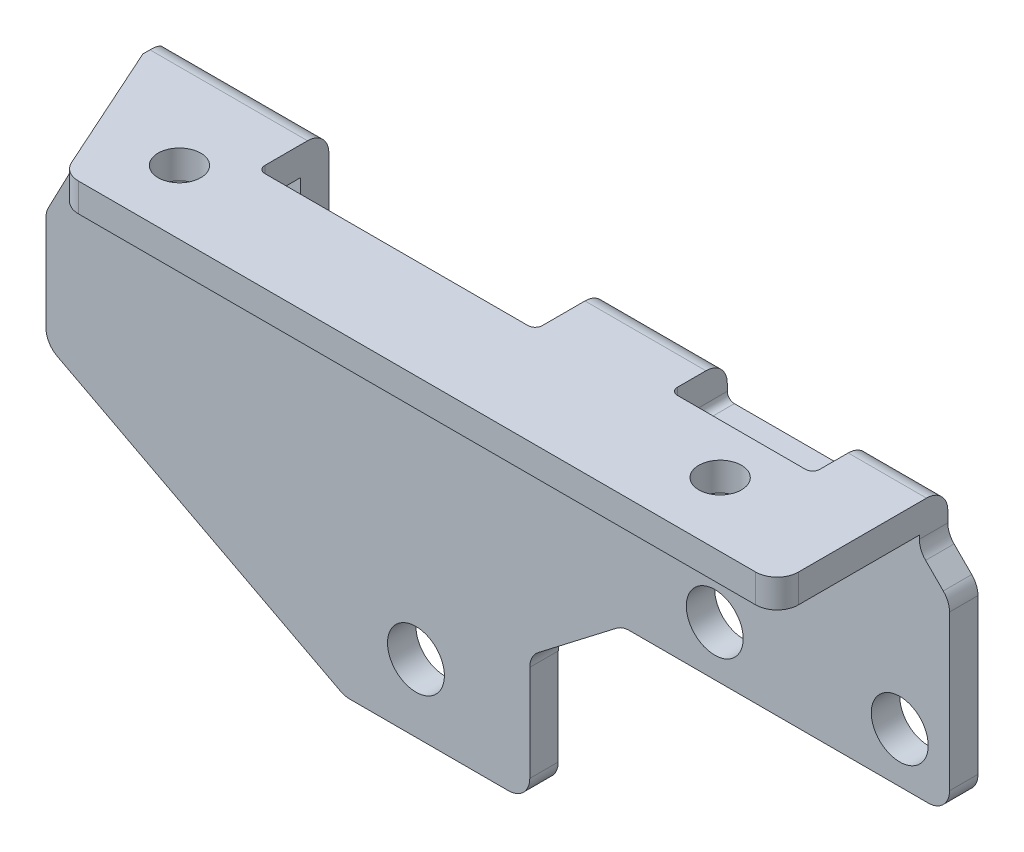
SolidWorks part; units mm, degrees
material "1060 Alloy"
ref_plane "Front Plane" through (0, 0, 0) normal (0, 0, 1) x (1, 0, 0)
ref_plane "Top Plane" through (0, 0, 0) normal (0, 1, 0) x (1, 0, 0)
ref_plane "Right Plane" through (0, 0, 0) normal (1, 0, 0) x (0, 0, -1)
sketch "Sketch1" plane through (0, 0, 0) normal (0, 0, 1) x (1, 0, 0)
  line L0 (0, 0) -> (21, -11)
  line L1 (21, -11) -> (27.7289, -11)
  line L2 (0, 0) -> (0, 8)
  line L3 (0, 8) -> (6.8095, 21)
  line L7 (63.5, 16) -> (63.5, 3)
  line L8 (63.5, 3) -> (40.5, 3)
  line L9 (40.5, 3) -> (34, -2)
  line L10 (34, -2) -> (34, -11)
  line L11 (34, -11) -> (27.7289, -11)
  line L12 (63.5, 16) -> (61.3787, 18.1213)
  line L13 (61.3787, 18.1213) -> (61.3787, 21)
  line L14 (61.3787, 21) -> (6.8095, 21)
  circle A0 centre (26, -6.25) radius 2
  circle A1 centre (47, 6.5) radius 2
  circle A2 centre (60, 6.5) radius 2
  circle A3 centre (7.5, 16) radius 2
  dimension "D12" = 4
  dimension "D13" = 4.75
  dimension "D14" = 8
  dimension "D15" = 4
  dimension "D16" = 3.5
  dimension "D17" = 3.5
  dimension "D18" = 13
  dimension "D19" = 4
  dimension "D20" = 7.5
  dimension "D21" = 27
  dimension "D1" = 13
  dimension "D2" = 9
  dimension "D3" = 21
  dimension "D4" = 11
  dimension "D5" = 8
  dimension "D6" = 13
  dimension "D7" = 5
  dimension "D8" = 6.5
  dimension "D9" = 23
  dimension "D10" = 13
  dimension "D11" = 3
extrude "Boss-Extrude1" add sketch "Sketch1" along normal blind 2
sketch "Sketch2" plane through (0, 0, 2) normal (0, 0, 1) x (1, 0, 0)
  line L1 (61.3787, 21) -> (6.8095, 21)
  line L2 (61.3787, 21) -> (61.3787, 19)
  line L3 (61.3787, 19) -> (6.8095, 19)
  line L4 (6.8095, 21) -> (6.8095, 19)
  dimension "D1" = 2
extrude "Boss-Extrude2" add sketch "Sketch2" along normal blind 10
sketch "Sketch3" plane through (0, 21, 0) normal (0, 1, 0) x (1, 0, 0)
  line L0 (6.8095, -2) -> (11.3095, -12)
  line L1 (61.3787, -12) -> (6.8095, -12) construction
  line L2 (11.3095, -12) -> (6.8095, -12)
  line L3 (6.8095, -12) -> (6.8095, -2)
  line L4 (61.3787, -12) -> (61.3787, 0) construction
  circle A0 centre (52.8787, -7.5) radius 1.5
  circle A1 centre (14.8787, -7.5) radius 1.5
  dimension "D2" = 3
  dimension "D3" = 8.5
  dimension "D4" = 4.5
  dimension "D5" = 38
  dimension "D1" = 4.5
extrude "Cut-Extrude1" cut sketch "Sketch3" against normal through all
sketch "Sketch4" plane through (0, 21, 0) normal (0, 1, 0) x (1, 0, 0)
  line L0 (61.3787, 0) -> (6.8095, 0) construction
  line L1 (17.8787, 0) -> (37.3787, 0)
  line L2 (17.8787, 0) -> (17.8787, -5)
  line L3 (17.8787, -5) -> (37.3787, -5)
  line L4 (37.3787, 0) -> (37.3787, -5)
  line L5 (61.3787, -12) -> (61.3787, 0) construction
  line L6 (55.8787, 0) -> (45.8787, 0)
  line L7 (55.8787, 0) -> (55.8787, -4)
  line L8 (55.8787, -4) -> (45.8787, -4)
  line L9 (45.8787, 0) -> (45.8787, -4)
  line L10 (61.3787, -12) -> (11.3095, -12) construction
  dimension "D1" = 5.5
  dimension "D2" = 8
  dimension "D3" = 10
  dimension "D4" = 7
  dimension "D5" = 8.5
  dimension "D6" = 19.5
extrude "Cut-Extrude2" cut sketch "Sketch4" against normal offset from surface (2.5 mm away) 15.5 up to face at (52, 3, 1)
sketch "Sketch5" plane through (0, 18.5, 0) normal (0, 1, 0) x (1, 0, 0)
  line L1 (17.8787, 0) -> (37.3787, 0)
  line L2 (17.8787, 0) -> (17.8787, -2)
  line L3 (17.8787, -2) -> (37.3787, -2)
  line L4 (37.3787, 0) -> (37.3787, -2)
extrude "Cut-Extrude3" cut sketch "Sketch5" against normal offset from surface (4.5 mm away) 25 up to face at (27.5, -11, 1)
fillet "Fillet1" radius 1.5 14 edges at (61.3787, 20, 12) (11.3095, 20, 12) (0, 8, 1) (0, 0, 1) (21, -11, 1) (34, -11, 1) (34, -2, 1) (40.5, 3, 1) (63.5, 3, 1) (61.3787, 18.1213, 1) (63.5, 16, 1) (12.3441, 21, 0) (41.6287, 21, 0) (58.6287, 21, 0)
fillet "Fillet2" radius 0.5 8 edges at (37.3787, 20, 5) (37.3787, 14, 1) (55.8787, 20, 4) (45.8787, 20, 4) (45.8787, 18.5, 1) (55.8787, 18.5, 1) (17.8787, 14, 1) (17.8787, 20, 5)
